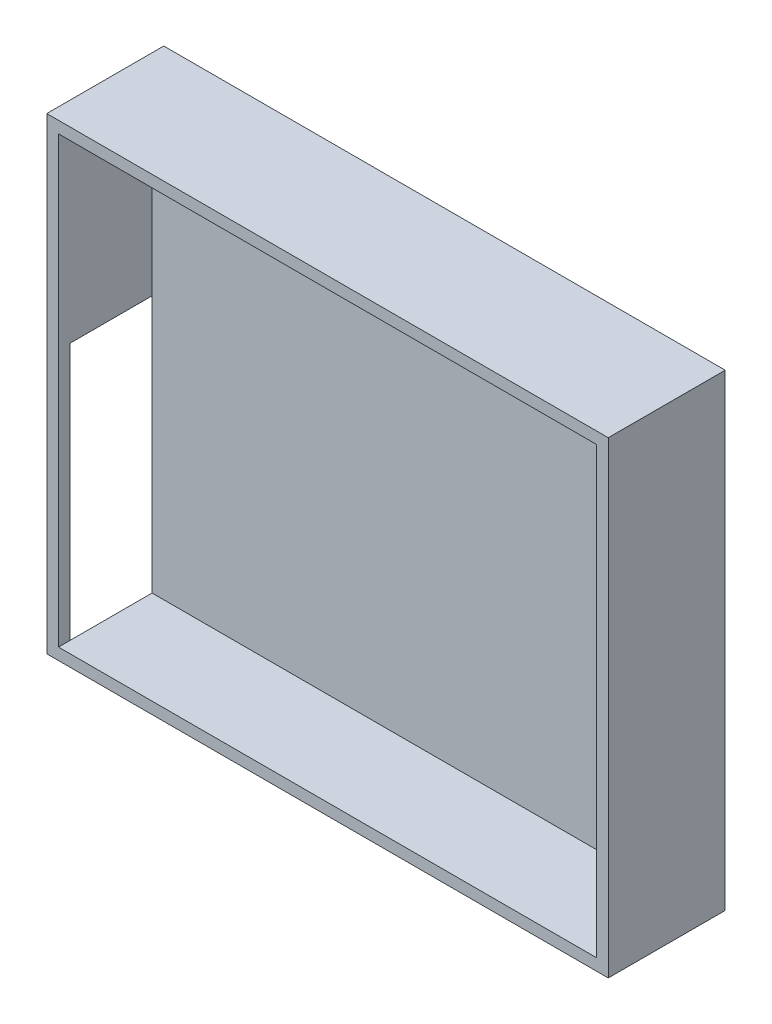
SolidWorks part; units mm, degrees
ref_plane "Front Plane" through (0, 0, 0) normal (0, 0, 1) x (1, 0, 0)
ref_plane "Top Plane" through (0, 0, 0) normal (0, 1, 0) x (1, 0, 0)
ref_plane "Right Plane" through (0, 0, 0) normal (1, 0, 0) x (0, 0, -1)
sketch "Sketch2" plane through (0, 0, 0) normal (0, 0, 1) x (1, 0, 0)
  line L1 (-60, 50) -> (60, 50)
  line L2 (-60, 50) -> (-60, -50)
  line L3 (-60, -50) -> (60, -50)
  line L4 (60, 50) -> (60, -50)
  line L5 (-60, 50) -> (60, -50) construction
  line L6 (-60, -50) -> (60, 50) construction
  point P0 (0, 0)
  dimension "D1" = 100
  dimension "D2" = 120
extrude "Boss-Extrude1" add sketch "Sketch2" along normal blind 25
sketch "Sketch3" plane through (0, 0, 25) normal (0, 0, 1) x (1, 0, 0)
  line L0 (0, 0) -> (0, 50) construction
  line L1 (60, 50) -> (-60, 50) construction
  line L2 (-60, -50) -> (-57.5, -50) construction
  line L3 (-60, -50) -> (60, -50) construction
  line L4 (-57.5, -50) -> (-57.5, -47.5) construction
  line L5 (60, -50) -> (60, 50) construction
  line L6 (-57.5, -47.5) -> (57.5, -47.5)
  line L7 (-57.5, -47.5) -> (-57.5, 47.5)
  line L8 (-57.5, 47.5) -> (57.5, 47.5)
  line L9 (57.5, -47.5) -> (57.5, 47.5)
  point P14 (-37.5, 2.5)
  point P15 (86.9454, 56.8981)
  dimension "D1" = 2.5
  dimension "D2" = 2.5
  dimension "D3" = 2.5
  dimension "D4" = 2.5
extrude "Cut-Extrude1" cut sketch "Sketch3" against normal blind 20
sketch "Sketch4" plane through (-60, 0, 0) normal (-1, 0, 0) x (0, 0, 1)
  line L0 (0, -60) -> (0, -52.5) construction
  line L1 (0, 50) -> (0, -50) construction
  line L2 (0, -52.5) -> (2.5, -52.5) construction
  line L3 (25, 50) -> (25, -50) construction
  line L4 (2.5, -52.5) -> (22.5, -52.5)
  line L5 (2.5, -52.5) -> (2.5, 7.5)
  line L6 (2.5, 7.5) -> (22.5, 7.5)
  line L7 (22.5, -52.5) -> (22.5, 7.5)
  dimension "D1" = 7.5
  dimension "D2" = 2.5
  dimension "D3" = 2.5
  dimension "D4" = 60
extrude "Cut-Extrude2" cut sketch "Sketch4" against normal up to surface (2.5 mm away) up to face at (-57.5, 0, 15)
